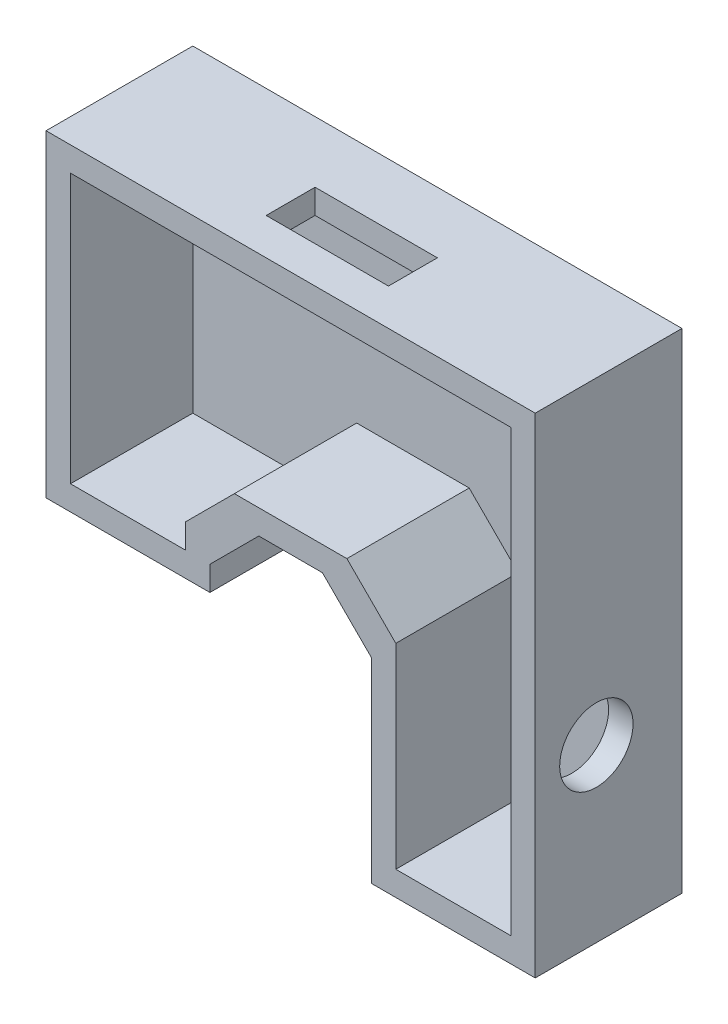
SolidWorks part; units mm, degrees
ref_plane "Front Plane" through (0, 0, 0) normal (0, 0, 1) x (1, 0, 0)
ref_plane "Top Plane" through (0, 0, 0) normal (0, 1, 0) x (1, 0, 0)
ref_plane "Right Plane" through (0, 0, 0) normal (1, 0, 0) x (0, 0, -1)
sketch "Sketch1" plane through (0, 0, 0) normal (0, 0, 1) x (1, 0, 0)
  line L0 (45, -45) -> (45, 45)
  line L1 (50, -50) -> (16.5, -50)
  line L2 (50, -50) -> (50, 50)
  line L3 (50, 50) -> (-50, 50)
  line L4 (-50, -15) -> (-50, 50)
  line L5 (50, -50) -> (-50, 50) construction
  line L7 (45, 45) -> (-45, 45)
  line L8 (-45, -10) -> (-45, 45)
  line L9 (45, -45) -> (21.5, -45)
  line L11 (16.5, -45) -> (16.5, -50)
  line L13 (45, -45) -> (-45, -45) construction
  line L15 (50, -50) -> (-50, -50) construction
  line L16 (-16.5, -15) -> (-16.5, 0)
  line L20 (-21.5, -10) -> (-45, -10)
  line L21 (-50, -15) -> (-16.5, -15)
  line L24 (16.5, -45) -> (16.5, 0)
  line L25 (21.5, -45) -> (21.5, 5)
  line L27 (-16.5, 0) -> (16.5, 0)
  line L29 (21.5, 5) -> (-21.5, 5)
  line L35 (-45, -45) -> (-45, 45) construction
  line L36 (-50, -50) -> (-50, 50) construction
  line L37 (-21.5, -10) -> (-21.5, 5)
  point P0 (0, 0)
  point P13 (0, 5)
  point P32 (-99.7812, 8.781)
  point P33 (-98.9404, 4.4572)
  point P35 (-22.5523, -19.5642)
  dimension "D2" = 100
  dimension "D5" = 60
  dimension "D9" = 5
  dimension "D3" = 5
extrude "Boss-Extrude1" add sketch "Sketch1" along normal mid plane 25
sketch "Sketch2" plane through (0, 0, -12.5) normal (0, 0, -1) x (-1, 0, 0)
  line L9 (-16.5, 0) -> (16.5, 0)
  line L10 (-16.5, 0) -> (-16.5, -50)
  line L12 (16.5, 0) -> (16.5, -15)
  line L13 (-16.5, -50) -> (-50, -50)
  line L14 (-50, -50) -> (-50, 50)
  line L15 (-50, 50) -> (50, 50)
  line L16 (50, 50) -> (50, -15)
  line L18 (16.5, -15) -> (50, -15)
  line L19 (50, -15) -> (16.5, -15) construction
  point P3 (0, -25)
  dimension "D1" = 33
extrude "Boss-Extrude2" add sketch "Sketch2" along normal blind 5
sketch "Sketch3" plane through (0, 45, 0) normal (0, -1, 0) x (1, 0, 0)
  line L1 (-12.5, -5) -> (12.5, -5)
  line L2 (-12.5, -5) -> (-12.5, 5)
  line L3 (-12.5, 5) -> (12.5, 5)
  line L4 (12.5, -5) -> (12.5, 5)
  line L5 (-12.5, -5) -> (12.5, 5) construction
  line L6 (-12.5, 5) -> (12.5, -5) construction
  point P0 (0, 0)
  dimension "D1" = 25
  dimension "D2" = 10
extrude "Cut-Extrude1" cut sketch "Sketch3" against normal through all
sketch "Sketch4" plane through (50, 0, 0) normal (1, 0, 0) x (0, 0, -1)
  line L0 (-12.5, -50) -> (17.5, -50) construction
  circle A0 centre (0, -15) radius 7.5
  point P4 (0, 0)
  dimension "D1" = 15
  dimension "D2" = 35
extrude "Cut-Extrude2" cut sketch "Sketch4" against normal blind 10 contours A0
chamfer "Chamfer2" distance 10 angle 45 2 edges at (16.5, 0, -2.5) (-16.5, 0, -2.5)
chamfer "Chamfer3" distance 10 angle 45 2 edges at (21.5, 5, 0) (-21.5, 5, 0)
